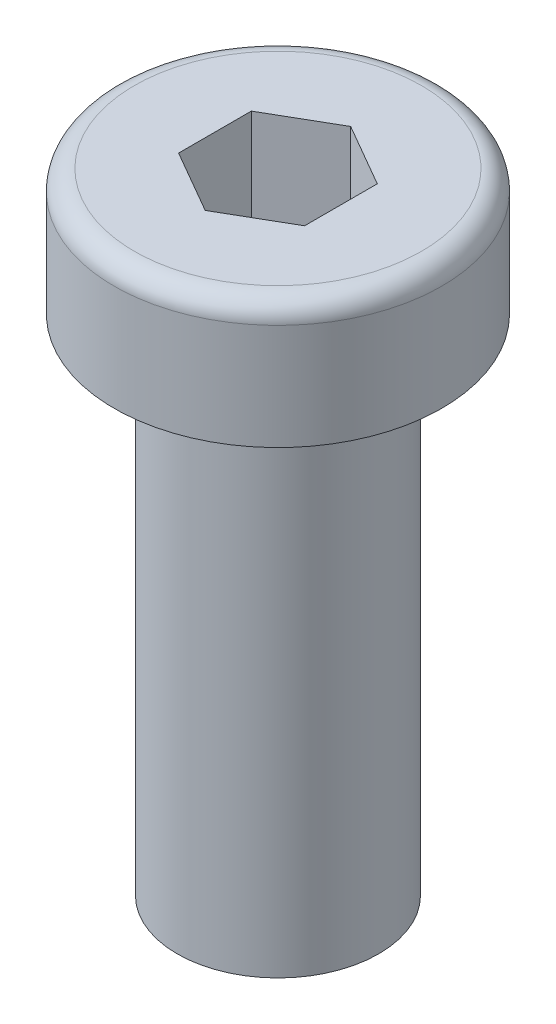
SolidWorks part; units mm, degrees
ref_plane "Front Plane" through (0, 0, 0) normal (0, 0, 1) x (1, 0, 0)
ref_plane "Top Plane" through (0, 0, 0) normal (0, 1, 0) x (1, 0, 0)
ref_plane "Right Plane" through (0, 0, 0) normal (1, 0, 0) x (0, 0, -1)
sketch "Sketch1" plane through (0, 0, 0) normal (0, 0, 1) x (1, 0, 0)
  line L0 (0, 25) -> (-5.7, 25)
  line L1 (-6.5, 24.2) -> (-6.5, 20)
  line L2 (-6.5, 20) -> (-4, 20)
  line L3 (-4, 20) -> (-4, 0)
  line L4 (-4, 0) -> (0, 0)
  line L5 (0, 0) -> (0, 25)
  arc A0 (-5.7, 25) -> (-6.5, 24.2) centre (-5.7, 24.2) ccw
  dimension "D5" = 0.8
  dimension "D1" = 5
  dimension "D2" = 6.5
  dimension "D3" = 20
  dimension "D4" = 4
revolve "Revolve1" add sketch "Sketch1" angle 360 about L5
sketch "Sketch2" plane through (0, 25, 0) normal (0, 1, 0) x (1, 0, 0)
  line L1 (0, 2.8868) -> (-2.5, 1.4434)
  line L2 (-2.5, 1.4434) -> (-2.5, -1.4434)
  line L3 (-2.5, -1.4434) -> (0, -2.8868)
  line L4 (0, -2.8868) -> (2.5, -1.4434)
  line L5 (2.5, -1.4434) -> (2.5, 1.4434)
  line L6 (2.5, 1.4434) -> (0, 2.8868)
  circle A0 centre (0, 0) radius 3
  circle A1 centre (0, 0) radius 2.5 construction
  dimension "D1" = 6
  dimension "D2" = 5
extrude "Cut-Extrude1" cut sketch "Sketch2" against normal blind 4.2 contours L1 L2 L3 L4 L5 L6
